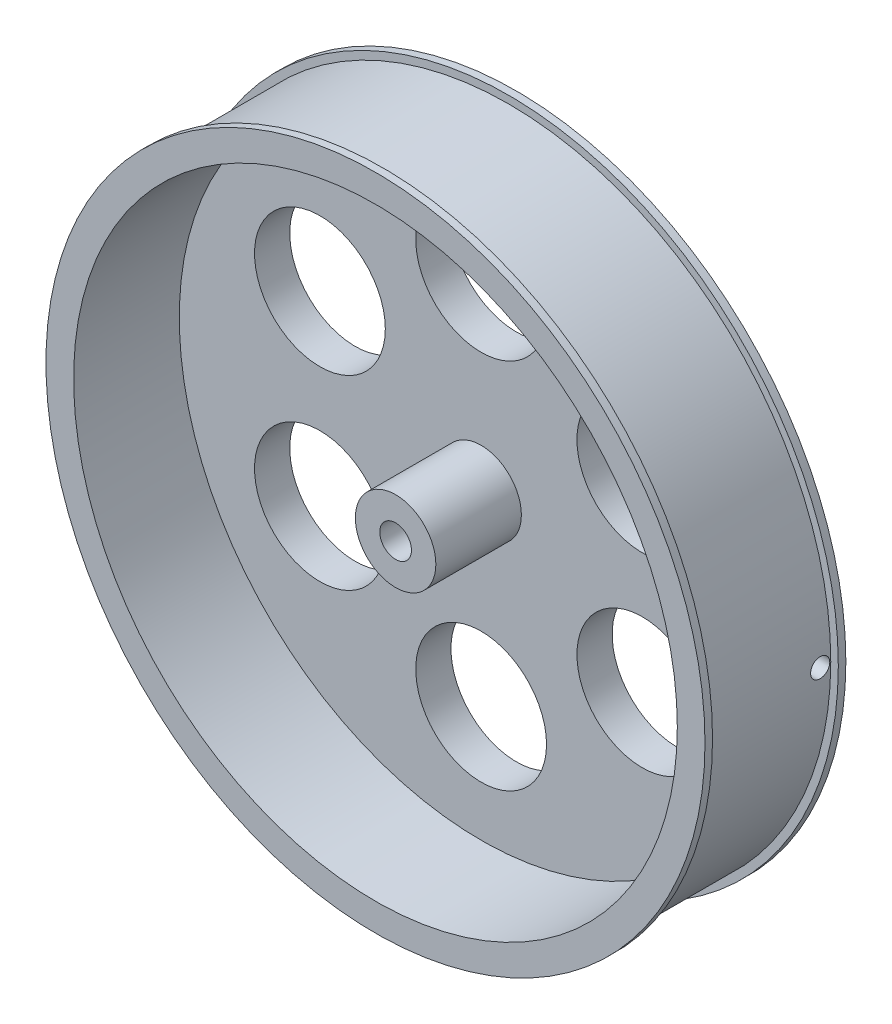
SolidWorks part; units mm, degrees
ref_plane "Front Plane" through (0, 0, 0) normal (0, 0, 1) x (1, 0, 0)
ref_plane "Top Plane" through (0, 0, 0) normal (0, 1, 0) x (1, 0, 0)
ref_plane "Right Plane" through (0, 0, 0) normal (1, 0, 0) x (0, 0, -1)
sketch "Sketch1" plane through (0, 0, 0) normal (0, 0, 1) x (1, 0, 0)
  circle A0 centre (0, 0) radius 64
  circle A1 centre (0, 0) radius 60
extrude "Rim" add sketch "Sketch1" along normal blind 28
sketch "Sketch2" plane through (0, 0, 0) normal (0, 0, 1) x (1, 0, 0)
  circle A0 centre (0, 0) radius 65.5
  circle A1 centre (0, 0) radius 63
extrude "Inner_bead_lip" add sketch "Sketch2" along normal blind 1.5
ref_plane "P_Front_26p5" through (0, 0, 26.5) normal (0, 0, 1) x (1, 0, 0)
sketch "Sketch3" plane through (0, 0, 26.5) normal (0, 0, 1) x (1, 0, 0)
  circle A0 centre (0, 0) radius 65.5
  circle A1 centre (0, 0) radius 63
extrude "Outer_bead_lip" add sketch "Sketch3" along normal blind 1.5
sketch "Sketch4" plane through (0, 0, 0) normal (0, 0, 1) x (1, 0, 0)
  circle A0 centre (0, 0) radius 61
extrude "Web" add sketch "Sketch4" along normal blind 7
sketch "Sketch5" plane through (0, 0, 0) normal (0, 0, 1) x (1, 0, 0)
  circle A0 centre (0, 0) radius 8
extrude "Hub_boss" add sketch "Sketch5" along normal blind 24
ref_plane "P_Front_m1" through (0, 0, -1) normal (0, 0, 1) x (1, 0, 0)
sketch "Sketch6" plane through (0, 0, -1) normal (0, 0, 1) x (1, 0, 0)
  circle A0 centre (32.0429, 18.5) radius 13
  circle A1 centre (0, 37) radius 13
  circle A2 centre (-32.0429, 18.5) radius 13
  circle A3 centre (-32.0429, -18.5) radius 13
  circle A4 centre (0, -37) radius 13
  circle A5 centre (32.0429, -18.5) radius 13
extrude "Lightening_holes" cut sketch "Sketch6" along normal blind 9
sketch "Sketch7" plane through (0, 0, -1) normal (0, 0, 1) x (1, 0, 0)
  circle A0 centre (0, 0) radius 3.15
extrude "Round_bore_6mm" cut sketch "Sketch7" along normal blind 30
sketch "Sketch8" plane through (0, 0, 0) normal (1, 0, 0) x (0, 0, -1)
  circle A0 centre (-3.6, 0) radius 1.3
extrude "Grub_screw_M3" cut sketch "Sketch8" along normal blind 9
ref_plane "P_Right_8p5" through (8.5, 0, 0) normal (1, 0, 0) x (0, 0, -1)
sketch "Sketch9" plane through (8.5, 0, 0) normal (1, 0, 0) x (0, 0, -1)
  circle A0 centre (-3.6, 0) radius 1.9
extrude "Grub_key_access" cut sketch "Sketch9" along normal blind 57.5
